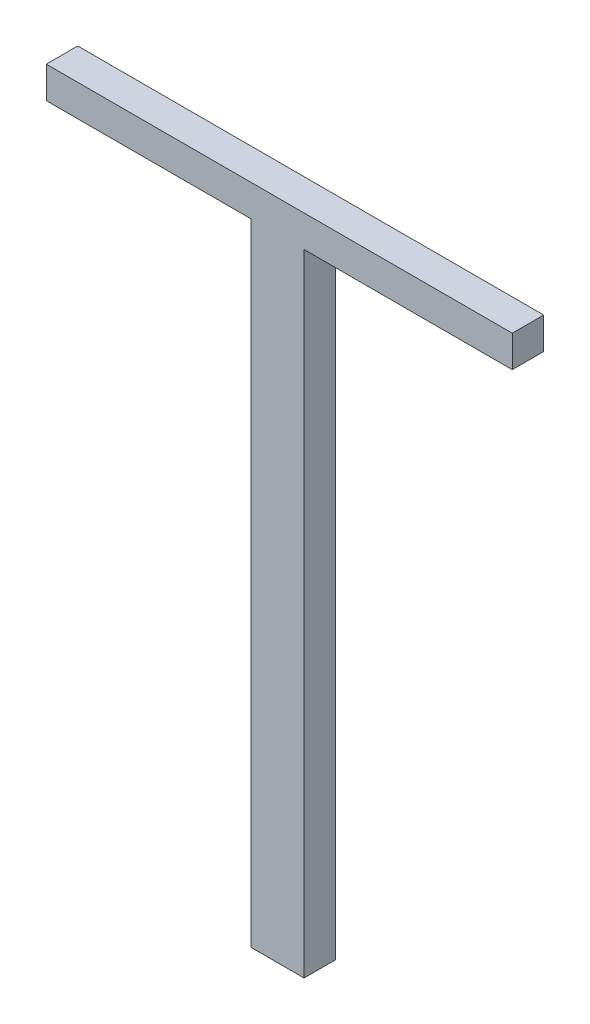
SolidWorks part; units mm, degrees
ref_plane "Спереди" through (0, 0, 0) normal (0, 0, 1) x (1, 0, 0)
ref_plane "Сверху" through (0, 0, 0) normal (0, 1, 0) x (1, 0, 0)
ref_plane "Справа" through (0, 0, 0) normal (1, 0, 0) x (0, 0, -1)
sketch "Эскиз1" plane through (0, 0, 0) normal (0, 0, 1) x (1, 0, 0)
  line L0 (-26.0359, -167.4967) -> (-26.0359, 835.7249)
  line L1 (-26.0359, 835.7249) -> (-351.793, 835.7249)
  line L2 (-351.793, 835.7249) -> (-351.793, 886.0077)
  line L3 (-351.793, 886.0077) -> (389.1147, 886.0077)
  line L4 (389.1147, 886.0077) -> (389.1147, 835.7249)
  line L5 (389.1147, 835.7249) -> (58.0187, 835.7249)
  line L6 (58.0187, 835.7249) -> (58.0187, -167.4967)
  line L7 (58.0187, -167.4967) -> (-26.0359, -167.4967)
extrude "Бобышка-Вытянуть1" add sketch "Эскиз1" along normal blind 50
